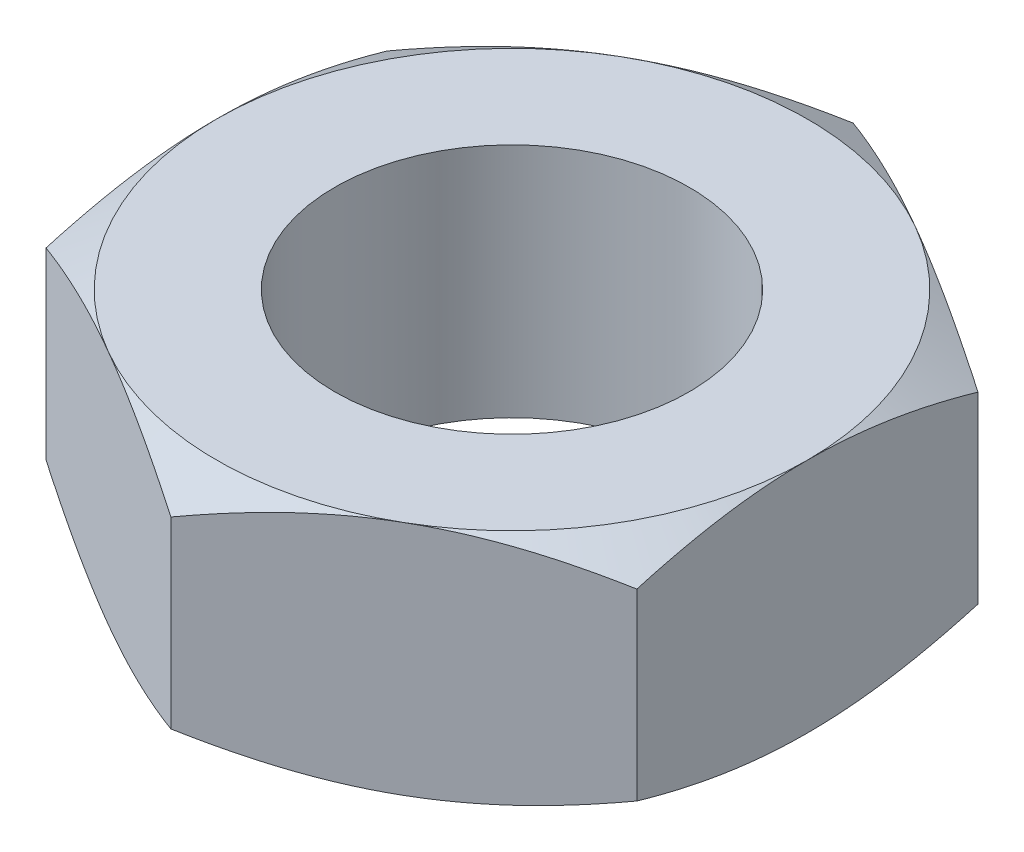
SolidWorks part; units mm, degrees
ref_plane "Front Plane" through (0, 0, 0) normal (0, 0, 1) x (1, 0, 0)
ref_plane "Top Plane" through (0, 0, 0) normal (0, 1, 0) x (1, 0, 0)
ref_plane "Right Plane" through (0, 0, 0) normal (1, 0, 0) x (0, 0, -1)
sketch "Sketch1" plane through (0, 0, 0) normal (0, 1, 0) x (1, 0, 0)
  line L1 (0, -2.8868) -> (2.5, -1.4434)
  line L2 (2.5, -1.4434) -> (2.5, 1.4434)
  line L3 (2.5, 1.4434) -> (0, 2.8868)
  line L4 (0, 2.8868) -> (-2.5, 1.4434)
  line L5 (-2.5, 1.4434) -> (-2.5, -1.4434)
  line L6 (-2.5, -1.4434) -> (0, -2.8868)
  circle A0 centre (0, 0) radius 1.5
  circle A1 centre (0, 0) radius 2.5 construction
  dimension "D1" = 3
  dimension "D2" = 5
extrude "Boss-Extrude1" add sketch "Sketch1" along normal blind 2
sketch "Sketch2" plane through (0, 2, 0) normal (0, 1, 0) x (1, 0, 0)
  circle A0 centre (0, 0) radius 2.5 construction
  circle A1 centre (0, 0) radius 2.5
extrude "Cut-Extrude1" cut sketch "Sketch2" against normal blind 2 draft 60 flip side to cut
sketch "Sketch3" plane through (0, 0, 0) normal (0, -1, 0) x (1, 0, 0)
  circle A0 centre (0, 0) radius 2.5 construction
  circle A1 centre (0, 0) radius 2.5
extrude "Cut-Extrude2" cut sketch "Sketch3" against normal blind 2 draft 60 flip side to cut
